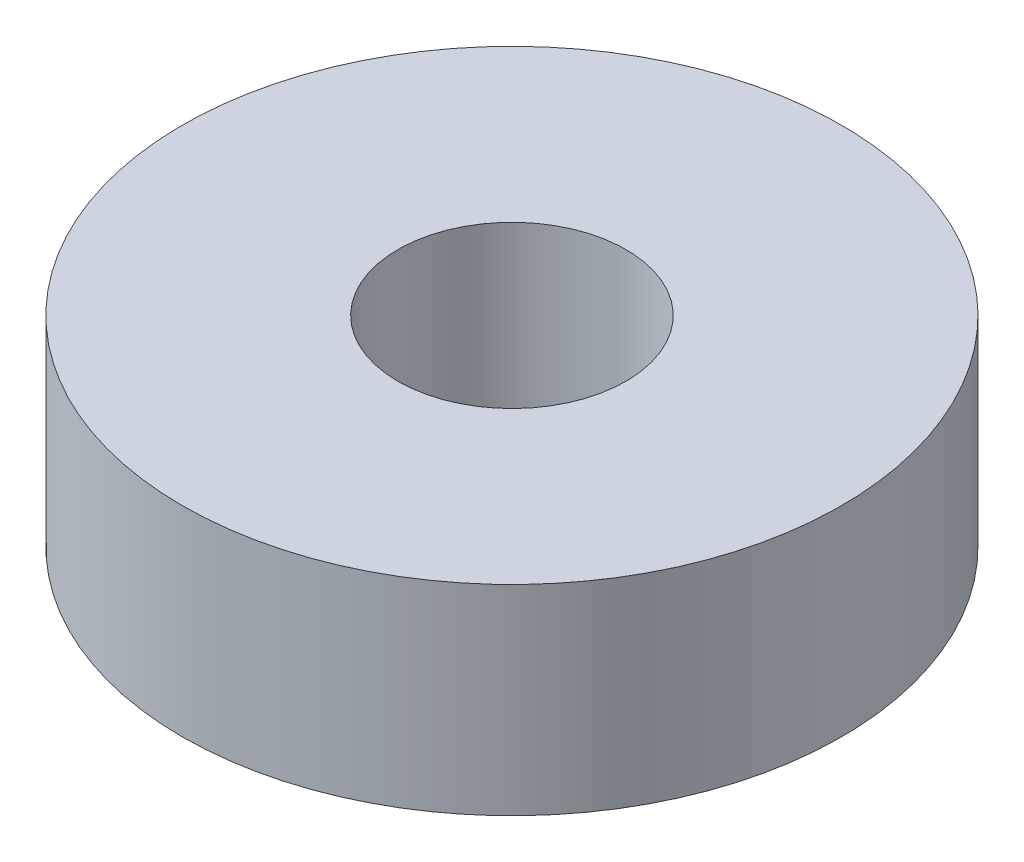
SolidWorks part; units mm, degrees
ref_plane "Front Plane" through (0, 0, 0) normal (0, 0, 1) x (1, 0, 0)
ref_plane "Top Plane" through (0, 0, 0) normal (0, 1, 0) x (1, 0, 0)
ref_plane "Right Plane" through (0, 0, 0) normal (1, 0, 0) x (0, 0, -1)
sketch "Sketch1" plane through (0, 0, 0) normal (0, 1, 0) x (1, 0, 0)
  circle A0 centre (0, 0) radius 13
  circle A1 centre (0, 0) radius 4.5
  dimension "D1" = 26
  dimension "D2" = 9
extrude "Boss-Extrude1" add sketch "Sketch1" along normal blind 7.9
